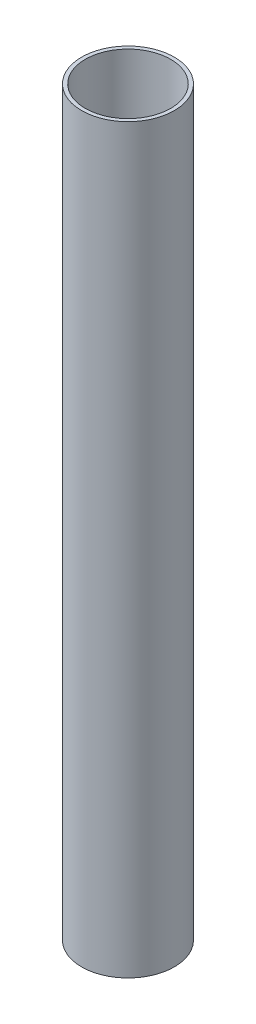
SolidWorks part; units mm, degrees
ref_plane "Front Plane" through (0, 0, 0) normal (0, 0, 1) x (1, 0, 0)
ref_plane "Top Plane" through (0, 0, 0) normal (0, 1, 0) x (1, 0, 0)
ref_plane "Right Plane" through (0, 0, 0) normal (1, 0, 0) x (0, 0, -1)
sketch "Sketch1" plane through (0, 0, 0) normal (0, 1, 0) x (1, 0, 0)
  circle A0 centre (0, 0) radius 12.5
  circle A1 centre (0, 0) radius 11.5
  dimension "D1" = 25
  dimension "D2" = 23
extrude "Boss-Extrude1" add sketch "Sketch1" along normal blind 200
